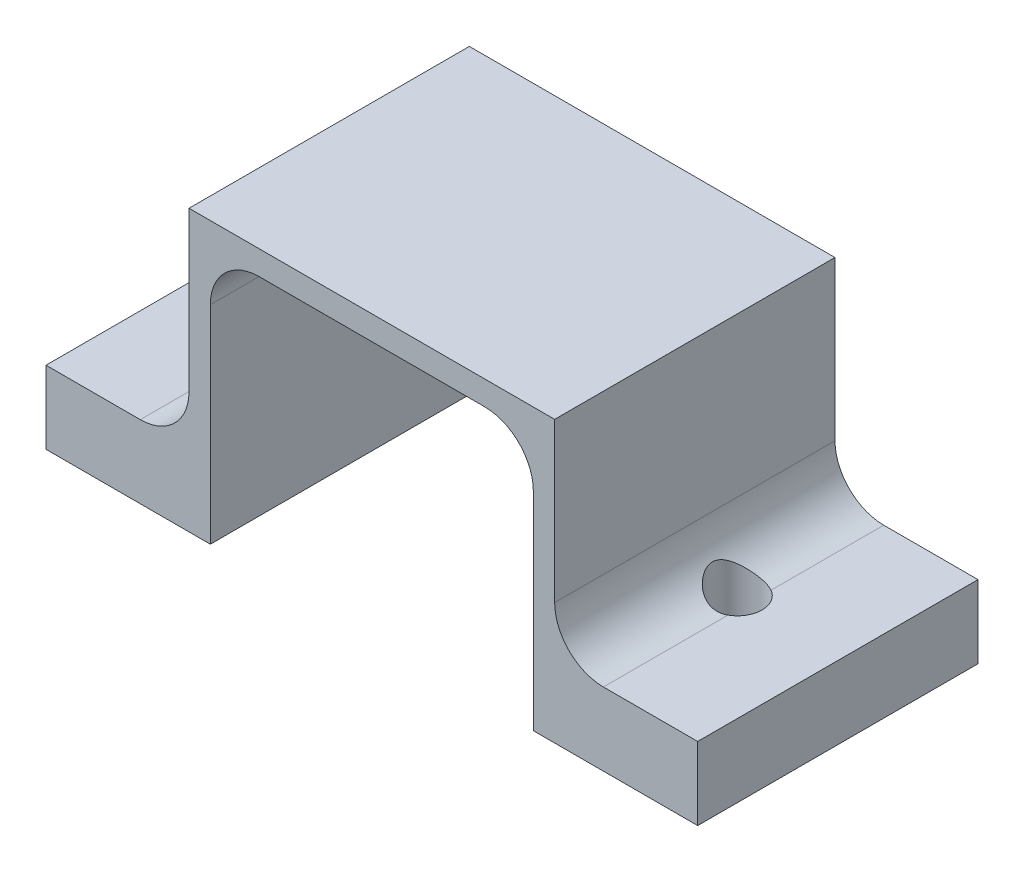
SolidWorks part; units mm, degrees
ref_plane "Front Plane" through (0, 0, 0) normal (0, 0, 1) x (1, 0, 0)
ref_plane "Top Plane" through (0, 0, 0) normal (0, 1, 0) x (1, 0, 0)
ref_plane "Right Plane" through (0, 0, 0) normal (1, 0, 0) x (0, 0, -1)
sketch "Sketch1" plane through (0, 0, 0) normal (0, 0, 1) x (1, 0, 0)
  line L0 (0, 9.5767) -> (0, 8.5767) construction
  line L1 (-7.5, 9.5767) -> (7.5, 9.5767)
  line L4 (13.3674, -1.9233) -> (13.3674, 1.0667)
  line L5 (13.3674, 1.0667) -> (9.5, 1.0667)
  line L6 (0, 9.5767) -> (0, 8.5868)
  line L7 (-4.6253, 8.5868) -> (4.6253, 8.5868)
  line L8 (6.6253, 6.5868) -> (6.6253, -1.9233)
  line L10 (6.6253, -1.9233) -> (13.3674, -1.9233)
  line L11 (7.5, 3.0667) -> (7.5, 9.5767)
  line L12 (0, 9.5767) -> (0, -3.004) construction
  line L13 (-7.5, 3.0667) -> (-7.5, 9.5767)
  line L14 (-6.6253, -1.9233) -> (-13.3674, -1.9233)
  line L15 (-6.6253, 6.5868) -> (-6.6253, -1.9233)
  line L16 (-13.3674, 1.0667) -> (-9.5, 1.0667)
  line L17 (-13.3674, -1.9233) -> (-13.3674, 1.0667)
  arc A0 (9.5, 1.0667) -> (7.5, 3.0667) centre (9.5, 3.0667) cw
  arc A1 (6.6253, 6.5868) -> (4.6253, 8.5868) centre (4.6253, 6.5868) ccw
  arc A2 (-6.6253, 6.5868) -> (-4.6253, 8.5868) centre (-4.6253, 6.5868) cw
  arc A3 (-9.5, 1.0667) -> (-7.5, 3.0667) centre (-9.5, 3.0667) ccw
  dimension "D3" = 2
  dimension "D2" = 2
  dimension "D1" = 11.5
  dimension "D4" = 7.5
extrude "Boss-Extrude1" add sketch "Sketch1" along normal blind 11.5 contours A1 L8 L10 L4 L5 A0 L11 L1 L6 L7 | A3 L16 L17 L14 L15 A2 L7 L6 L1 L13
sketch "Sketch2" plane through (0, 1.0667, 0) normal (0, 1, 0) x (1, 0, 0)
  line L0 (0, 0) -> (0, -11.5) construction
  line L1 (-7.5, -11.5) -> (7.5, -11.5) construction
  circle A0 centre (-9, -5.5077) radius 1.016
  circle A1 centre (9, -5.5077) radius 1.016
  dimension "D1" = 2.032
  dimension "D2" = 18
extrude "Cut-Extrude2" cut sketch "Sketch2" against normal through all both and the other way through all
